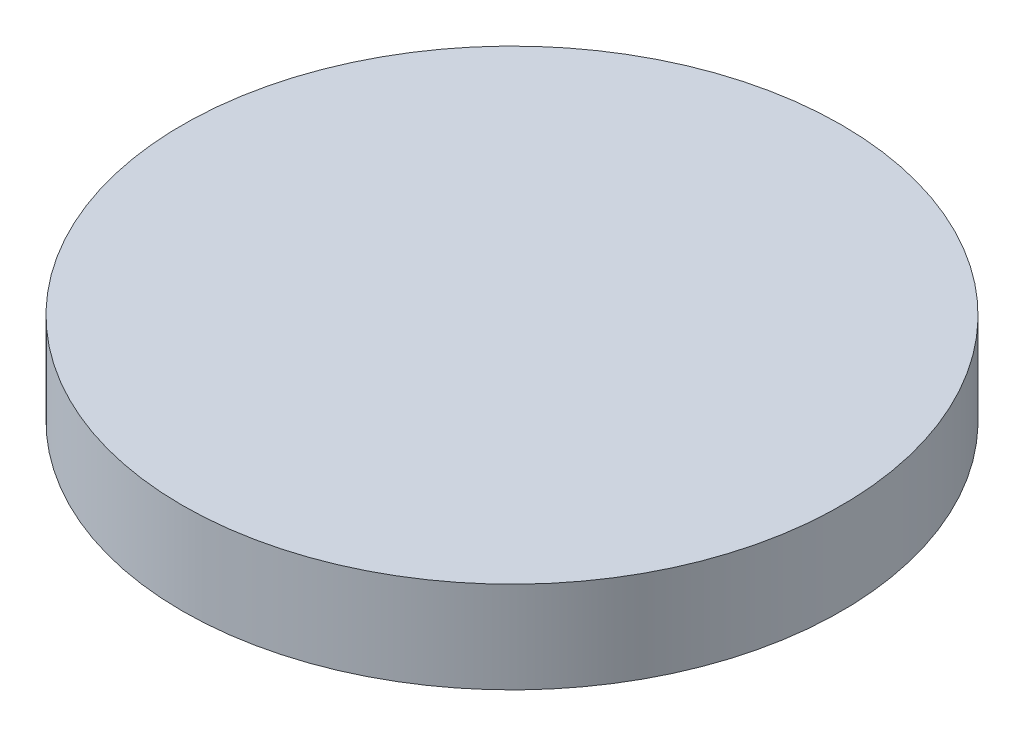
SolidWorks part; units mm, degrees
ref_plane "前视基准面" through (0, 0, 0) normal (0, 0, 1) x (1, 0, 0)
ref_plane "上视基准面" through (0, 0, 0) normal (0, 1, 0) x (1, 0, 0)
ref_plane "右视基准面" through (0, 0, 0) normal (1, 0, 0) x (0, 0, -1)
sketch "草图1" plane through (0, 0, 0) normal (0, 1, 0) x (1, 0, 0)
  circle A0 centre (0, 0) radius 18
  dimension "D1" = 36
extrude "凸台-拉伸1" add sketch "草图1" along normal blind 5
